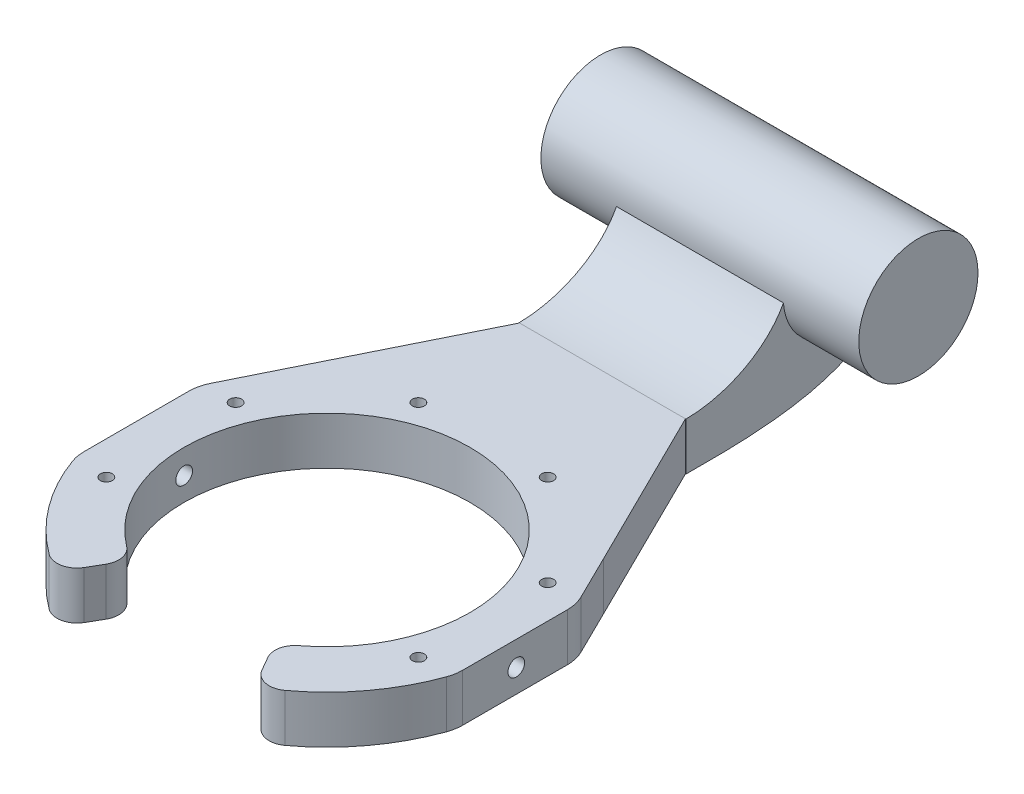
SolidWorks part; units mm, degrees
other "Markup1"
sketch "Sketch28"
ref_plane "前视基准面" through (0, 0, 0) normal (0, 0, 1) x (1, 0, 0)
ref_plane "上视基准面" through (0, 0, 0) normal (0, 1, 0) x (1, 0, 0)
ref_plane "右视基准面" through (0, 0, 0) normal (1, 0, 0) x (0, 0, -1)
sketch "Sketch1" plane through (0, 0, 0) normal (0, 1, 0) x (1, 0, 0)
  line L0 (0, 0) -> (0, 37.0754) construction
  line L1 (-20.8826, 69.3254) -> (20.8826, 69.3254)
  line L2 (-20.8826, 69.3254) -> (-41.057, 28.5363)
  line L3 (-47.6377, 15.187) -> (-47.6377, -15.187)
  line L4 (47.6377, 15.187) -> (47.6377, -15.187)
  line L5 (20.8826, 69.3254) -> (41.057, 28.5363)
  arc A0 (-41.057, 28.5363) -> (-47.6377, 15.187) centre (0, 0) ccw
  arc A1 (-47.6377, -15.187) -> (47.6377, -15.187) centre (0, 0) ccw
  arc A2 (47.6377, 15.187) -> (41.057, 28.5363) centre (0, 0) ccw
  dimension "D2" = 50
extrude "Boss-Extrude1" add sketch "Sketch1" along normal blind 12
sketch "Sketch2" plane through (0, 0, 0) normal (0, -1, 0) x (1, 0, 0)
  line L0 (-31.575, 0) -> (31.575, 0) construction
  line L1 (-20.2, -24.2681) -> (20.2, -24.2681) construction
  line L2 (-20.2, 24.2681) -> (20.2, 24.2681) construction
  circle A0 centre (0, 0) radius 31.575 construction
  circle A7 centre (0, 0) radius 18
  dimension "D1" = 63.15
extrude "Cut-Extrude1" cut sketch "Sketch2" against normal blind 12
sketch "Sketch4" plane through (0, 0, 0) normal (1, 0, 0) x (0, 0, -1)
  line L0 (69.3254, 12) -> (69.3254, 0)
  line L1 (121.3953, 17.9383) -> (96.2538, 34.3061) construction
  line L5 (82.9017, 12) -> (55.7492, 12) construction
  line L6 (88.7476, 0) -> (49.6456, 0) construction
  arc A2 (121.3953, 17.9383) -> (96.2538, 34.3061) centre (108.8246, 26.1222) cw
  spline S0 degree 3 poles (69.3254, 12) (80.639, 12) (95.8206, 18.9104) (96.2538, 34.3061) knots 0 0 0 0 1 1 1 1
  spline S1 degree 3 poles (69.3254, 0) (85.6179, 0) (116.3671, -0.7025) (121.3953, 17.9383) knots 0 0 0 0 1 1 1 1
  point P12 (95.4547, 34.8264)
  point P13 (121.3953, 17.9383)
  dimension "D1" = 30
extrude "Boss-Extrude2" add sketch "Sketch4" along normal mid plane 42
sketch "Sketch8" plane through (0, 0, 0) normal (1, 0, 0) x (0, 0, -1)
  line L0 (121.3953, 17.9383) -> (96.2538, 34.3061) construction
  circle A0 centre (108.8246, 26.1222) radius 15
extrude "Boss-Extrude4" add sketch "Sketch8" along normal mid plane 80
sketch "Sketch9" plane through (0, 0, 0) normal (1, 0, 0) x (0, 0, -1)
  line L0 (31.3899, 12) -> (31.3899, 0) construction
  line L1 (31.3899, 0) -> (31.3899, 6) construction
  line L2 (31.3899, 6) -> (-55, 6) construction
  line L4 (0, 0) -> (0, 12) construction
  line L5 (18, 12) -> (-18, 12) construction
  circle A4 centre (0, 6) radius 2.5
sketch "Sketch12" plane through (0, 12, 0) normal (0, 1, 0) x (1, 0, 0)
  line L0 (0, 42.5) -> (0, 0) construction
  line L1 (0, 0) -> (-16.264, 39.2649) construction
  circle A0 centre (0, 0) radius 42.5 construction
  circle A1 centre (-16.264, 39.2649) radius 1.5
  circle A2 centre (16.264, 39.2649) radius 1.5
  circle A3 centre (39.2649, 16.264) radius 1.5
  circle A4 centre (39.2649, -16.264) radius 1.5
  circle A7 centre (-39.2649, -16.264) radius 1.5
  circle A8 centre (-39.2649, 16.264) radius 1.5
  circle A9 centre (-16.264, -39.2649) radius 1.5 [skipped]
  circle A10 centre (16.264, -39.2649) radius 1.5 [skipped]
  point P22 (0, 0)
  dimension "D1" = 85
  dimension "D3" = 8
  dimension "D2" = 22.5
extrude "Cut-Extrude3" cut sketch "Sketch12" against normal through all
sketch "Sketch13" plane through (0, 12, 0) normal (0, 1, 0) x (1, 0, 0)
  circle A0 centre (0, 0) radius 36
  dimension "D1" = 72
extrude "Cut-Extrude4" cut sketch "Sketch13" against normal through all
sketch "Sketch14" plane through (0, 12, 0) normal (0, 1, 0) x (1, 0, 0)
  line L0 (0, 0) -> (-48.7821, -84.493)
  line L1 (0, 0) -> (48.7821, -84.493)
  arc A0 (-48.7821, -84.493) -> (48.7821, -84.493) centre (0, 0) ccw
  point P5 (0, -97.5642)
  dimension "D1" = 60
extrude "Cut-Extrude5" cut sketch "Sketch14" against normal through all
sketch "Sketch25" plane through (47.6377, 0, 0) normal (1, 0, 0) x (0, 0, -1)
  line L0 (0, 12) -> (0, 0)
  line L1 (-15.187, 12) -> (15.187, 12) construction
  circle A0 centre (0, 6) radius 2.5
  dimension "D1" = 15.187
fillet "Fillet1" radius 5 4 edges at (-25, 6, 43.3013) (-18, 6, 31.1769) (18, 6, 31.1769) (25, 6, 43.3013)
sketch "Sketch26" plane through (-47.6377, 0, 0) normal (-1, 0, 0) x (0, 0, 1)
  line L0 (0, 12) -> (0, 0)
  line L1 (-15.187, 12) -> (15.187, 12) construction
  line L2 (-15.187, 12) -> (-15.187, 0) construction
  circle A0 centre (0, 6) radius 2.5
  dimension "D1" = 15.187
hole_wizard "M5 Tapped Hole1" positions "3DSketch2" profile "Sketch29" tap size "M5" standard "GB" end condition through all
sketch3d "3DSketch2"
  line L0 (-47.6377, 12, -15.187) -> (-47.6377, 0, -15.187) construction
  line L1 (-47.6377, 5.8654, 0) -> (-47.6377, 53.8629, 0)
  line L5 (-47.6377, 5.8654, 0) -> (0, 0, 0)
  point P0 (-47.6377, 5.8654, 0)
  dimension "D1" = 15.187
sketch "Sketch29" plane through (-47.6377, 5.8654, 0) normal (0, 1, 0) x (0, 0, 1)
  line L0 (0, 0) -> (0, 95.2755)
  line L1 (0, 95.2755) -> (2.1, 95.2755)
  line L2 (2.1, 95.2755) -> (2.1, 0)
  line L5 (2.1, 0) -> (0, 0)
  line L11 (0, -6.35) -> (0, 107.95) construction
  dimension "Thru Tap Drill Dia." = 4.2
  dimension "Thru Tap Drill Depth" = 95.2755
cosmetic thread "Hole Thread1" parameters "D2"=5
cosmetic thread "Cosmetic Thread1" parameters "D2"=5
cosmetic thread "Cosmetic Thread2" parameters "D2"=5
sketch "Sketch30" plane through (0, 12, 0) normal (0, 1, 0) x (1, 0, 0)
  line L0 (-41.057, 28.5363) -> (-47.6377, 15.187)
  line L1 (-47.6377, 15.187) -> (-55.0941, 25.3219)
  line L2 (-55.0941, 25.3219) -> (-41.057, 28.5363)
  line L3 (41.057, 28.5363) -> (47.6377, 15.187)
  line L4 (47.6377, 15.187) -> (61.9445, 29.1546)
  line L5 (61.9445, 29.1546) -> (41.057, 28.5363)
extrude "Cut-Extrude6" cut sketch "Sketch30" against normal through all
fillet "Fillet2" radius 10 6 edges at (41.057, 6, -28.5363) (-41.057, 6, -28.5363) (-47.6377, 6, -15.187) (-47.6377, 6, 15.187) (47.6377, 6, 15.187) (47.6377, 6, -15.187)
